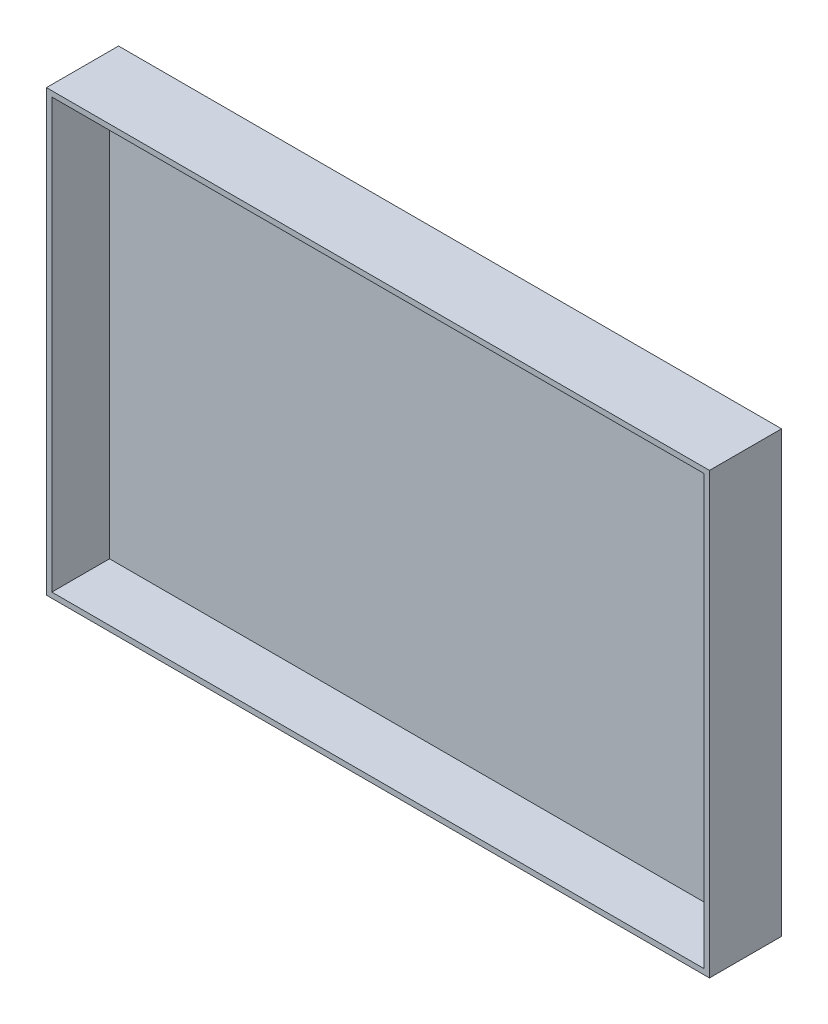
SolidWorks part; units mm, degrees
ref_plane "Front Plane" through (0, 0, 0) normal (0, 0, 1) x (1, 0, 0)
ref_plane "Top Plane" through (0, 0, 0) normal (0, 1, 0) x (1, 0, 0)
ref_plane "Right Plane" through (0, 0, 0) normal (1, 0, 0) x (0, 0, -1)
sketch "Sketch1" plane through (0, 0, 0) normal (0, 0, 1) x (1, 0, 0)
  line L1 (-45.25, -29.75) -> (45.25, -29.75)
  line L2 (-45.25, -29.75) -> (-45.25, 29.75)
  line L3 (-45.25, 29.75) -> (45.25, 29.75)
  line L4 (45.25, -29.75) -> (45.25, 29.75)
  line L5 (-45.25, -29.75) -> (45.25, 29.75) construction
  line L6 (-45.25, 29.75) -> (45.25, -29.75) construction
  line L7 (46, -30.5) -> (-46, -30.5)
  line L8 (46, -30.5) -> (46, 30.5)
  line L9 (46, 30.5) -> (-46, 30.5)
  line L10 (-46, -30.5) -> (-46, 30.5)
  line L11 (46, -30.5) -> (-46, 30.5) construction
  line L12 (46, 30.5) -> (-46, -30.5) construction
  point P0 (0, 0)
  point P6 (0, 0)
  dimension "D1" = 90.5
  dimension "D2" = 59.5
  dimension "D3" = 61
  dimension "D4" = 92
extrude "Boss-Extrude1" add sketch "Sketch1" along normal blind 10
sketch "Sketch2" plane through (0, 0, 0) normal (0, 0, 1) x (1, 0, 0)
  line L1 (-46, -30.5) -> (46, -30.5)
  line L2 (-46, -30.5) -> (-46, 30.5)
  line L3 (-46, 30.5) -> (46, 30.5)
  line L4 (46, -30.5) -> (46, 30.5)
  line L5 (-46, -30.5) -> (46, 30.5) construction
  line L6 (-46, 30.5) -> (46, -30.5) construction
  point P0 (0, 0)
extrude "Boss-Extrude2" add sketch "Sketch2" along normal blind 2
